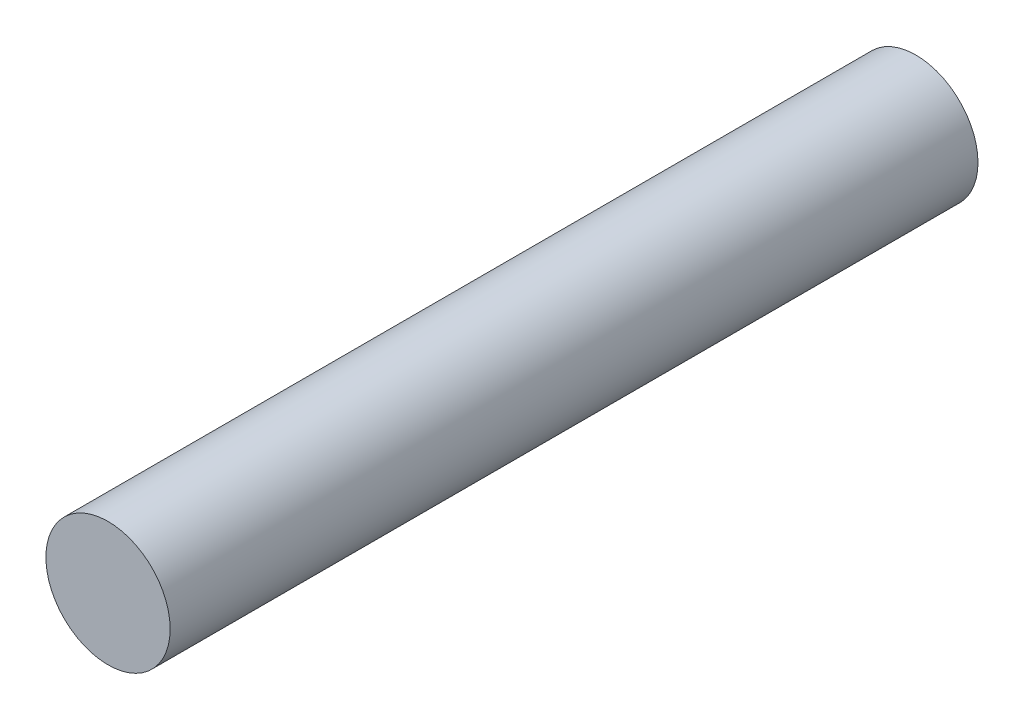
SolidWorks part; units mm, degrees
ref_plane "Front" through (0, 0, 0) normal (0, 0, 1) x (1, 0, 0)
ref_plane "Top" through (0, 0, 0) normal (0, 1, 0) x (1, 0, 0)
ref_plane "Right" through (0, 0, 0) normal (1, 0, 0) x (0, 0, -1)
sketch "Sketch1" plane through (0, 0, 0) normal (0, 0, 1) x (1, 0, 0)
  circle A0 centre (0, 0) radius 2.54
  dimension "D1" = 5.08
extrude "Boss-Extrude1" add sketch "Sketch1" along normal blind 33.02
sketch "Sketch2" plane through (0, 0, 33.02) normal (0, 0, 1) x (1, 0, 0)
  circle A0 centre (0, 0) radius 0.4445
  dimension "D1" = 0.889
